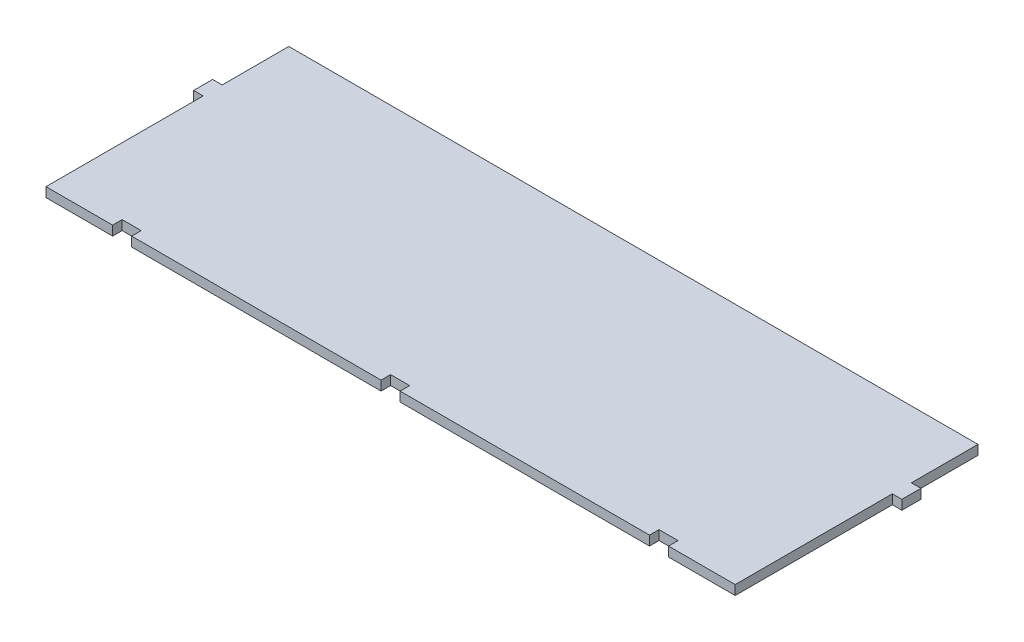
SolidWorks part; units mm, degrees
ref_plane "Front Plane" through (0, 0, 0) normal (0, 0, 1) x (1, 0, 0)
ref_plane "Top Plane" through (0, 0, 0) normal (0, 1, 0) x (1, 0, 0)
ref_plane "Right Plane" through (0, 0, 0) normal (1, 0, 0) x (0, 0, -1)
sketch "Sketch1" plane through (0, 0, 0) normal (0, 1, 0) x (1, 0, 0)
  line L0 (-186, 33.695) -> (-181, 33.695)
  line L1 (181, 68.695) -> (-181, 68.695)
  line L2 (186, 33.695) -> (186, 23.695)
  line L3 (181, -58.845) -> (146, -58.845)
  line L4 (-186, 33.695) -> (-186, 23.695)
  line L5 (-146, -58.845) -> (-146, -53.845)
  line L6 (-146, -53.845) -> (-136, -53.845)
  line L7 (-181, 68.695) -> (-181, 33.695)
  line L8 (-181, 23.695) -> (-186, 23.695)
  line L9 (186, 33.695) -> (181, 33.695)
  line L10 (181, 68.695) -> (181, 33.695)
  line L11 (181, 23.695) -> (186, 23.695)
  line L12 (-181, 23.695) -> (-181, -58.845)
  line L13 (181, 23.695) -> (181, -58.845)
  line L14 (-136, -53.845) -> (-136, -58.845)
  line L15 (146, -58.845) -> (146, -53.845)
  line L16 (146, -53.845) -> (136, -53.845)
  line L17 (136, -53.845) -> (136, -58.845)
  line L18 (-5, -53.845) -> (5, -53.845)
  line L19 (5, -53.845) -> (5, -58.845)
  line L20 (-5, -53.845) -> (-5, -58.845)
  line L21 (-5, -58.845) -> (-136, -58.845)
  line L22 (-146, -58.845) -> (-181, -58.845)
  line L23 (136, -58.845) -> (5, -58.845)
  point P0 (0, 0)
  point P24 (0, -53.845)
  point P25 (0, 68.695)
  dimension "D1" = 5
  dimension "D2" = 35
  dimension "D3" = 5
  dimension "D4" = 35
  dimension "D5" = 10
  dimension "D6" = 5
  dimension "D7" = 35
  dimension "D8" = 10
  dimension "D9" = 10
  dimension "D10" = 372
  dimension "D11" = 127.54
  dimension "D12" = 35
  dimension "D13" = 10
  dimension "D14" = 5
  dimension "D15" = 10
  dimension "D16" = 82.54
  dimension "D17" = 5
  dimension "D18" = 131
extrude "Boss-Extrude1" add sketch "Sketch1" along normal blind 5
